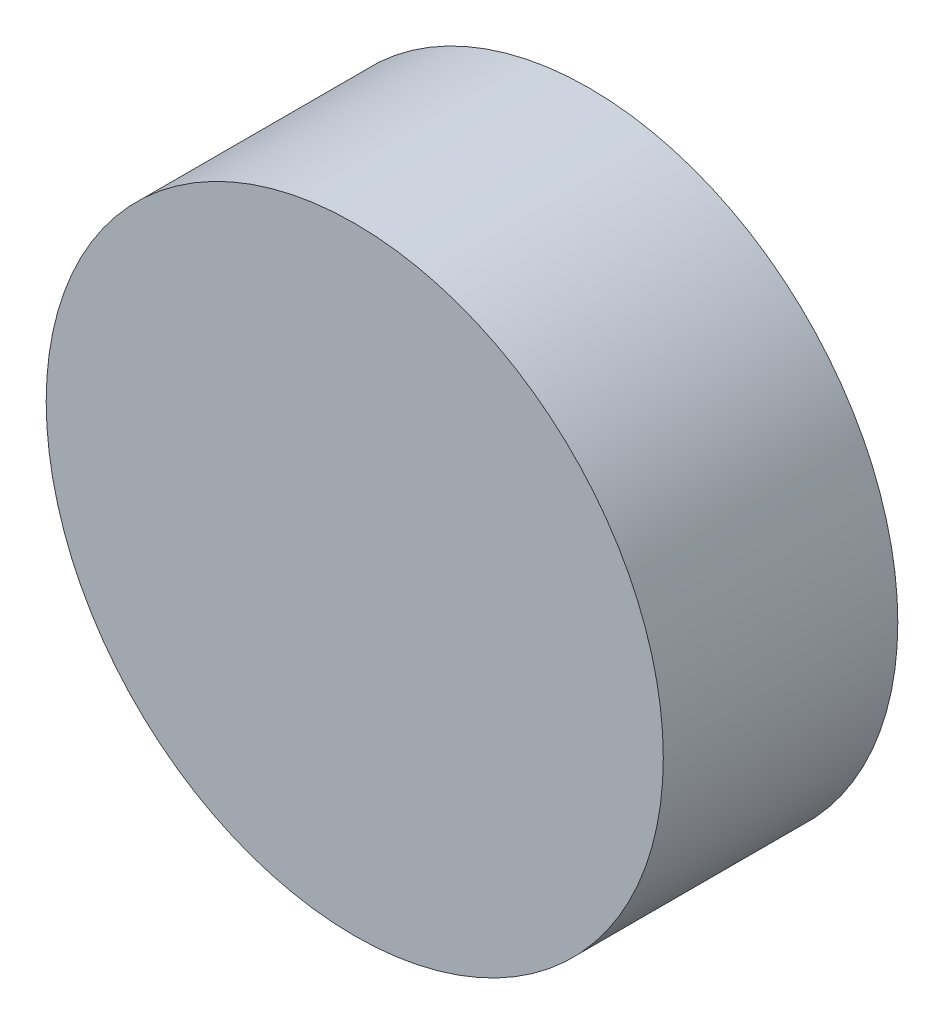
SolidWorks part; units mm, degrees
ref_plane "Спереди" through (0, 0, 0) normal (0, 0, 1) x (1, 0, 0)
ref_plane "Сверху" through (0, 0, 0) normal (0, 1, 0) x (1, 0, 0)
ref_plane "Справа" through (0, 0, 0) normal (1, 0, 0) x (0, 0, -1)
sketch "Эскиз1" plane through (0, 0, 0) normal (0, 0, 1) x (1, 0, 0)
  circle A0 centre (0, 0) radius 12.5
  circle A1 centre (0, 0) radius 25
extrude "Вытянуть2" add sketch "Эскиз1" along normal blind 15
sketch "Эскиз4" plane through (0, 0, 15) normal (0, 0, 1) x (1, 0, 0)
  circle A0 centre (0, 0) radius 25
extrude "Вытянуть3" add sketch "Эскиз4" along normal blind 4
